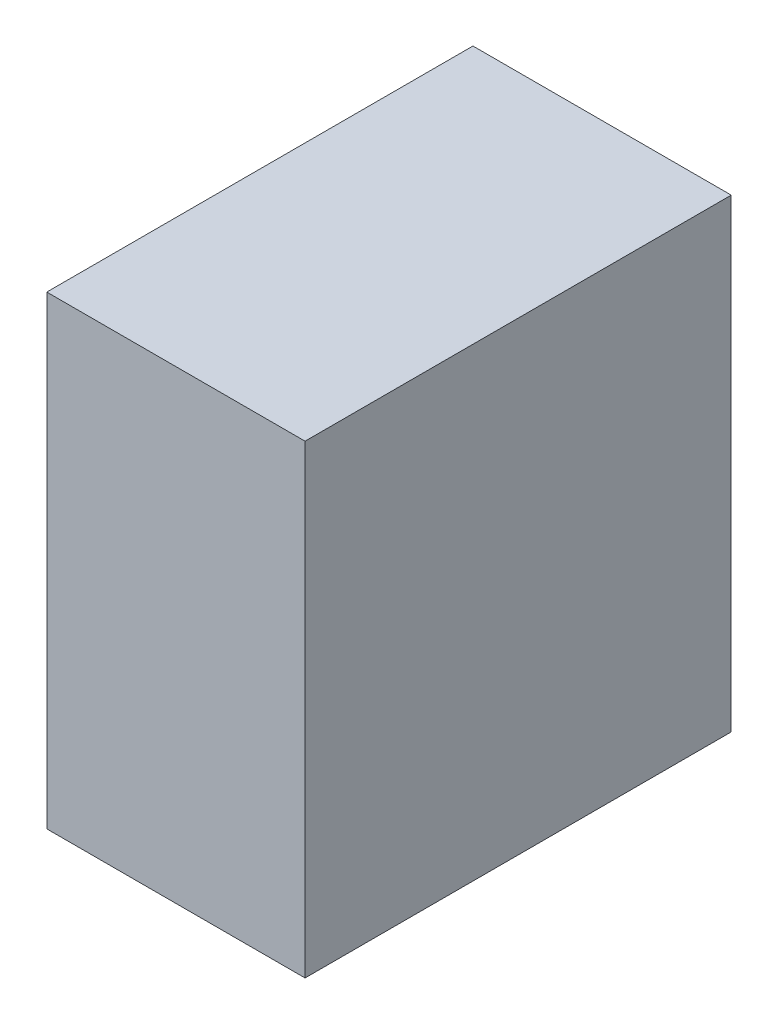
SolidWorks part; units mm, degrees
ref_plane "Front Plane" through (0, 0, 0) normal (0, 0, 1) x (1, 0, 0)
ref_plane "Top Plane" through (0, 0, 0) normal (0, 1, 0) x (1, 0, 0)
ref_plane "Right Plane" through (0, 0, 0) normal (1, 0, 0) x (0, 0, -1)
sketch "Sketch1" plane through (0, 0, 0) normal (0, 1, 0) x (1, 0, 0)
  line L0 (-10, -16.5) -> (-10, 16.5)
  line L1 (-8.5, -15) -> (8.5, -15)
  line L2 (-8.5, -15) -> (-8.5, 15)
  line L3 (-8.5, 15) -> (8.5, 15)
  line L4 (8.5, -15) -> (8.5, 15)
  line L5 (-8.5, -15) -> (8.5, 15) construction
  line L6 (-8.5, 15) -> (8.5, -15) construction
  line L7 (-10, 16.5) -> (10, 16.5)
  line L8 (10, -16.5) -> (10, 16.5)
  line L9 (-10, -16.5) -> (10, -16.5)
  point P0 (0, 0)
  dimension "D1" = 30
  dimension "D2" = 17
  dimension "D3" = 1.5
extrude "Boss-Extrude1" add sketch "Sketch1" along normal blind 35
sketch "Sketch2" plane through (0, 35, 0) normal (0, 1, 0) x (1, 0, 0)
  line L4 (-10, -16.5) -> (10, -16.5)
  line L5 (10, -16.5) -> (10, 16.5)
  line L6 (10, 16.5) -> (-10, 16.5)
  line L7 (-10, 16.5) -> (-10, -16.5)
  line L8 (-10, -16.5) -> (10, -16.5)
  line L9 (10, -16.5) -> (10, 16.5)
  line L10 (10, 16.5) -> (-10, 16.5)
  line L11 (-10, 16.5) -> (-10, -16.5)
  dimension "D1" = 0
extrude "Boss-Extrude2" add sketch "Sketch2" along normal blind 1
sketch "Sketch3" plane through (0, 0, 0) normal (0, -1, 0) x (1, 0, 0)
  line L0 (8.5, -15) -> (-8.5, -15) construction
  line L1 (-2, -15) -> (-3.5, -15)
  line L2 (-2, -15) -> (-2, -13)
  line L3 (-2, -13) -> (-3.5, -13)
  line L4 (-3.5, -15) -> (-3.5, -13)
  line L5 (0, -16.5) -> (0, 16.5) construction
  line L6 (10, -16.5) -> (-10, -16.5) construction
  line L7 (-10, 16.5) -> (10, 16.5) construction
  line L8 (2, -15) -> (2, -13)
  line L9 (3.5, -15) -> (3.5, -13)
  line L10 (2, -13) -> (3.5, -13)
  line L11 (2, -15) -> (3.5, -15)
  line L12 (-8.5, 0) -> (8.5, 0) construction
  line L13 (-8.5, -15) -> (-8.5, 15) construction
  line L14 (8.5, 15) -> (8.5, -15) construction
  line L15 (2, 13) -> (3.5, 13)
  line L16 (3.5, 15) -> (3.5, 13)
  line L17 (2, 15) -> (3.5, 15)
  line L18 (2, 15) -> (2, 13)
  line L19 (-2, 15) -> (-2, 13)
  line L20 (-2, 15) -> (-3.5, 15)
  line L21 (-3.5, 15) -> (-3.5, 13)
  line L22 (-2, 13) -> (-3.5, 13)
  dimension "D1" = 2
  dimension "D2" = 1.5
  dimension "D3" = 2
extrude "Boss-Extrude3" add sketch "Sketch3" against normal up to surface (35 mm away) up to face at (0, 35, 0)
